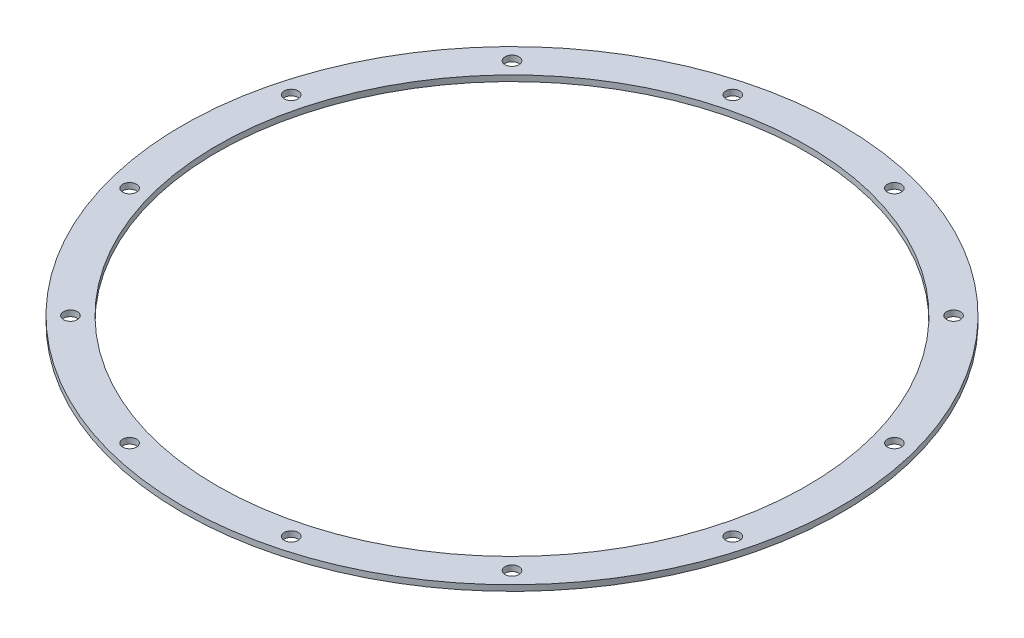
SolidWorks part; units mm, degrees
material "AISI 304"
ref_plane "Piano frontale" through (0, 0, 0) normal (0, 0, 1) x (1, 0, 0)
ref_plane "Piano superiore" through (0, 0, 0) normal (0, 1, 0) x (1, 0, 0)
ref_plane "Piano destro" through (0, 0, 0) normal (1, 0, 0) x (0, 0, -1)
sketch "Schizzo1" plane through (0, 0, 0) normal (0, 1, 0) x (1, 0, 0)
  line L0 (300, 0) -> (-300, 0) construction
  line L1 (0, -300) -> (0, 300) construction
  circle A0 centre (0, 0) radius 255
  arc A1 (-285, 0) -> (285, 0) centre (0, 0) ccw
  circle A2 centre (0, 0) radius 270 construction
  circle A3 centre (-260.8, 69.8811) radius 6
  circle A4 centre (-190.9188, 190.9188) radius 6
  circle A5 centre (-69.8811, 260.8) radius 6
  circle A6 centre (69.8811, 260.8) radius 6
  circle A7 centre (190.9188, 190.9188) radius 6
  circle A8 centre (260.8, 69.8811) radius 6
  circle A9 centre (260.8, -69.8811) radius 6
  circle A10 centre (190.9188, -190.9188) radius 6
  circle A11 centre (69.8811, -260.8) radius 6
  circle A12 centre (-69.8811, -260.8) radius 6
  circle A13 centre (-190.9188, -190.9188) radius 6
  circle A14 centre (-260.8, -69.8811) radius 6
  arc A15 (285, 0) -> (-285, 0) centre (0, 0) ccw
  point P7 (0, 0)
  point P11 (-385, -300)
  point P34 (0, 0)
  point P36 (0, 0)
  point P37 (-385, 300)
  dimension "D1" = 12
extrude "Estrusione-Estrusione1" add sketch "Schizzo1" along normal mid plane 5
sketch "Schizzo2" plane through (0, 2.5, 0) normal (0, 1, 0) x (1, 0, 0)
  line L0 (0, -125) -> (0, 125) construction
  line L1 (125, 0) -> (-125, 0) construction
  point P4 (0, 0)
  point P8 (0, 0)
